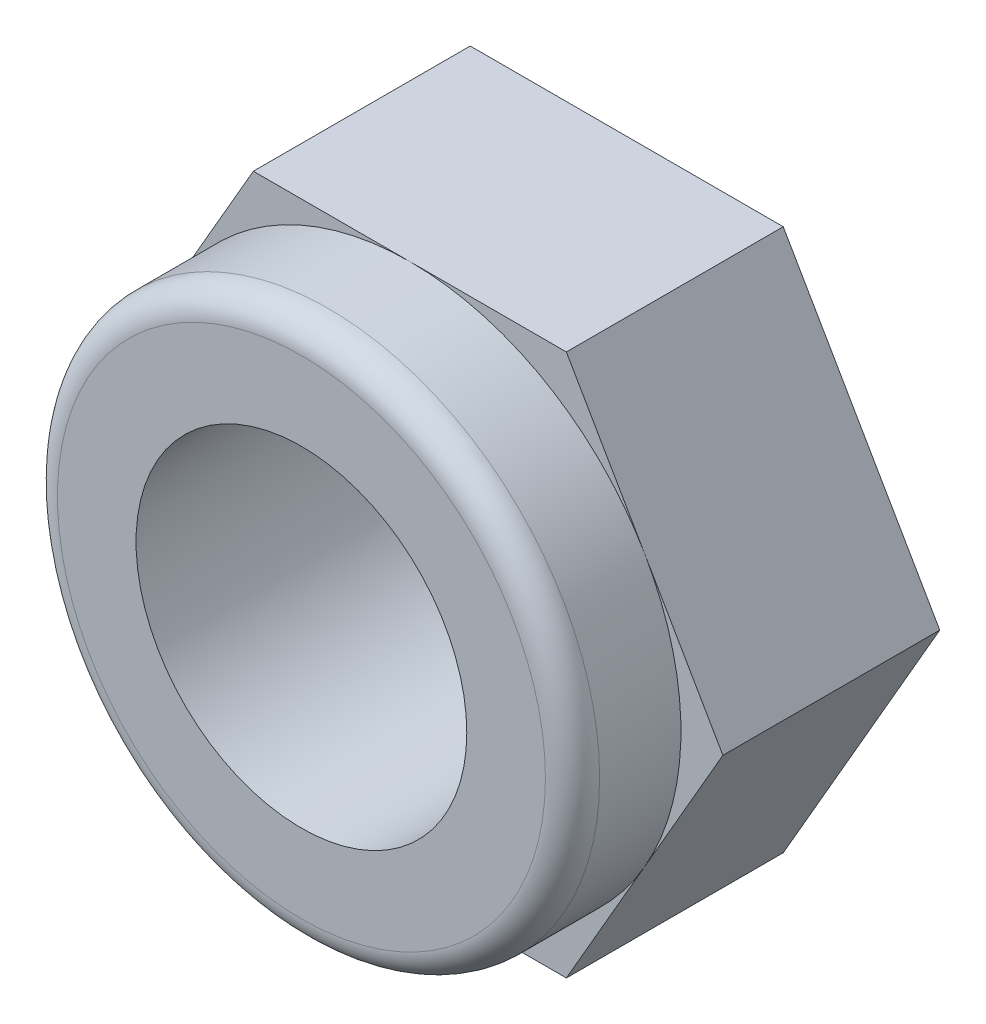
SolidWorks part; units mm, degrees
ref_plane "Front Plane" through (0, 0, 0) normal (0, 0, 1) x (1, 0, 0)
ref_plane "Top Plane" through (0, 0, 0) normal (0, 1, 0) x (1, 0, 0)
ref_plane "Right Plane" through (0, 0, 0) normal (1, 0, 0) x (0, 0, -1)
sketch "Sketch1" plane through (0, 0, 0) normal (0, 0, 1) x (1, 0, 0)
  line L1 (-2.8868, -0.1) -> (-5.7735, -5.1)
  line L2 (-5.7735, -5.1) -> (-2.8868, -10.1)
  line L3 (-2.8868, -10.1) -> (2.8868, -10.1)
  line L4 (2.8868, -10.1) -> (5.7735, -5.1)
  line L5 (5.7735, -5.1) -> (2.8868, -0.1)
  line L6 (2.8868, -0.1) -> (-2.8868, -0.1)
  circle A0 centre (0, -5.1) radius 3.05 construction
  circle A1 centre (0, -5.1) radius 3.05
  circle A2 centre (0, -5.1) radius 5 construction
  dimension "D1" = 10
extrude "Boss-Extrude1" add sketch "Sketch1" along normal blind 4
sketch "Sketch2" plane through (0, 0, 4) normal (0, 0, 1) x (1, 0, 0)
  line L0 (-5.7735, -5.1) -> (-2.8868, -10.1) construction
  circle A0 centre (0, -5.1) radius 3.05 construction
  circle A1 centre (0, -5.1) radius 3.05
  circle A2 centre (0, -5.1) radius 5
extrude "Boss-Extrude2" add sketch "Sketch2" along normal blind 2
fillet "Fillet1" radius 0.5 1 edges at (5, -5.1, 6)
